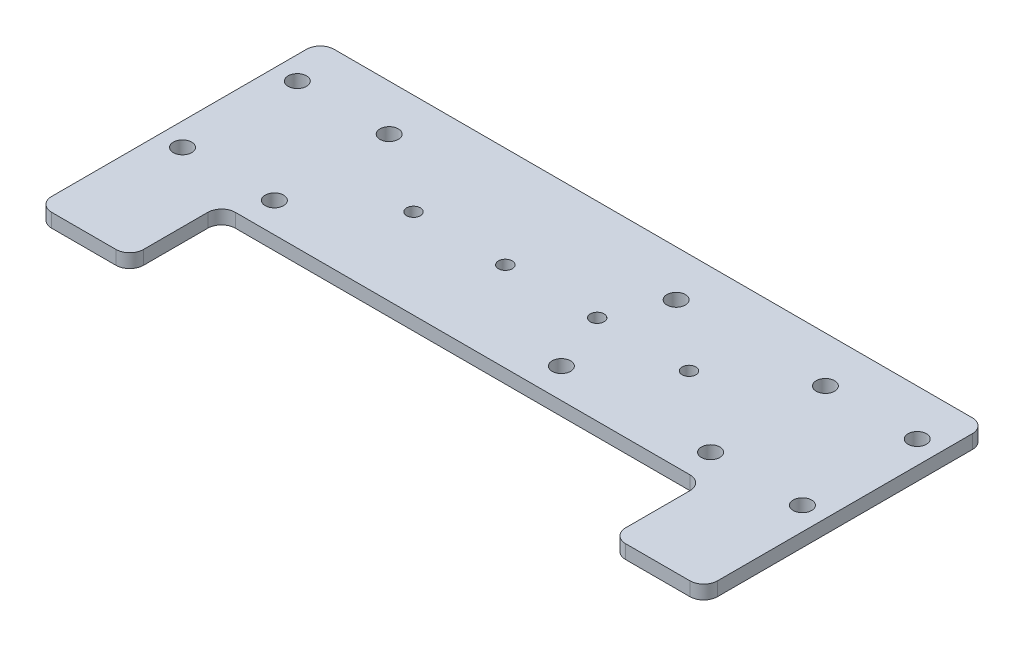
SolidWorks part; units mm, degrees
material "Thornel Mat VMA"
ref_plane "前视基准面" through (0, 0, 0) normal (0, 0, 1) x (1, 0, 0)
ref_plane "上视基准面" through (0, 0, 0) normal (0, 1, 0) x (1, 0, 0)
ref_plane "右视基准面" through (0, 0, 0) normal (1, 0, 0) x (0, 0, -1)
other "Configuration Table"
sketch "草图1" plane through (0, 0, 0) normal (0, 1, 0) x (1, 0, 0)
  line L0 (-72.5, 22.5) -> (-72.5, -39)
  line L1 (67.5, -12.5) -> (-67.5, -12.5) construction
  line L2 (67.5, -12.5) -> (67.5, 12.5) construction
  line L3 (67.5, 12.5) -> (-67.5, 12.5) construction
  line L4 (-67.5, -12.5) -> (-67.5, 12.5) construction
  line L5 (67.5, -12.5) -> (-67.5, 12.5) construction
  line L6 (67.5, 12.5) -> (-67.5, -12.5) construction
  line L7 (15, -12.5) -> (-72.5, -12.5) construction
  line L8 (15, -12.5) -> (15, 12.5) construction
  line L9 (15, 12.5) -> (-72.5, 12.5) construction
  line L11 (15, -12.5) -> (-72.5, 10.5263) construction
  line L12 (15, 12.5) -> (-72.5, -10.5263) construction
  line L13 (72.5, 22.5) -> (-72.5, 22.5)
  line L14 (72.5, 22.5) -> (72.5, -39)
  line L15 (72.5, -39) -> (-72.5, -39)
  line L17 (72.5, 22.5) -> (-72.5, -33.0607) construction
  line L18 (72.5, -39) -> (-72.5, 16.5607) construction
  line L19 (47.5, -12.5) -> (-47.5, -12.5) construction
  line L20 (47.5, -12.5) -> (47.5, 12.5) construction
  line L21 (47.5, 12.5) -> (-47.5, 12.5) construction
  line L22 (-47.5, -12.5) -> (-47.5, 12.5) construction
  line L23 (47.5, -12.5) -> (-47.5, 12.5) construction
  line L24 (47.5, 12.5) -> (-47.5, -12.5) construction
  circle A0 centre (-67.5, 12.5) radius 2
  circle A1 centre (-67.5, -12.5) radius 2
  circle A2 centre (67.5, 12.5) radius 2
  circle A3 centre (67.5, -12.5) radius 2
  circle A6 centre (15, 12.5) radius 2
  circle A7 centre (15, -12.5) radius 2
  circle A8 centre (-47.5, 12.5) radius 2
  circle A9 centre (-47.5, -12.5) radius 2
  circle A10 centre (47.5, 12.5) radius 2
  circle A11 centre (47.5, -12.5) radius 2
  point P0 (0, 0)
  point P10 (-32.5, 0)
  point P19 (0, 0)
  point P24 (0, 0)
  dimension "D3" = 4
  dimension "D12" = 95
  dimension "D1" = 135
  dimension "D2" = 25
  dimension "D4" = 145
  dimension "D8" = 5
  dimension "D10" = 10
  dimension "D11" = 61.5
extrude "凸台-拉伸1" add sketch "草图1" along normal blind 3
fillet "圆角1" radius 3 4 edges at (72.5, 1.5, -22.5) (72.5, 1.5, 39) (-72.5, 1.5, 39) (-72.5, 1.5, -22.5)
sketch "草图4" plane through (0, 3, 0) normal (0, 1, 0) x (1, 0, 0)
  line L0 (-52.5, -39) -> (-52.5, -19)
  line L1 (-69.5, -39) -> (69.5, -39) construction
  line L2 (-52.5, -19) -> (52.5, -19)
  line L3 (52.5, -19) -> (52.5, -39)
  line L4 (52.5, -39) -> (-52.5, -39)
  dimension "D1" = 105
  dimension "D2" = 52.5
  dimension "D3" = 20
extrude "切除-拉伸3" cut sketch "草图4" against normal blind 6
sketch "草图6" plane through (0, 3, 0) normal (0, 1, 0) x (1, 0, 0)
  line L0 (52.5, -19) -> (-52.5, -19) construction
  circle A2 centre (-30.2, 0.5) radius 1.5
  circle A3 centre (-10.2, 0.5) radius 1.5
  circle A4 centre (9.8, 0.5) radius 1.5
  circle A5 centre (29.8, 0.5) radius 1.5
  dimension "D1" = 19.5
  dimension "D2" = 3
  dimension "D4" = 4
  dimension "D3" = 30.2
  dimension "D5" = 20
extrude "切除-拉伸6" cut sketch "草图6" against normal through all
fillet "圆角3" radius 3 4 edges at (52.5, 1.5, 19) (52.5, 1.5, 39) (-52.5, 1.5, 19) (-52.5, 1.5, 39)
